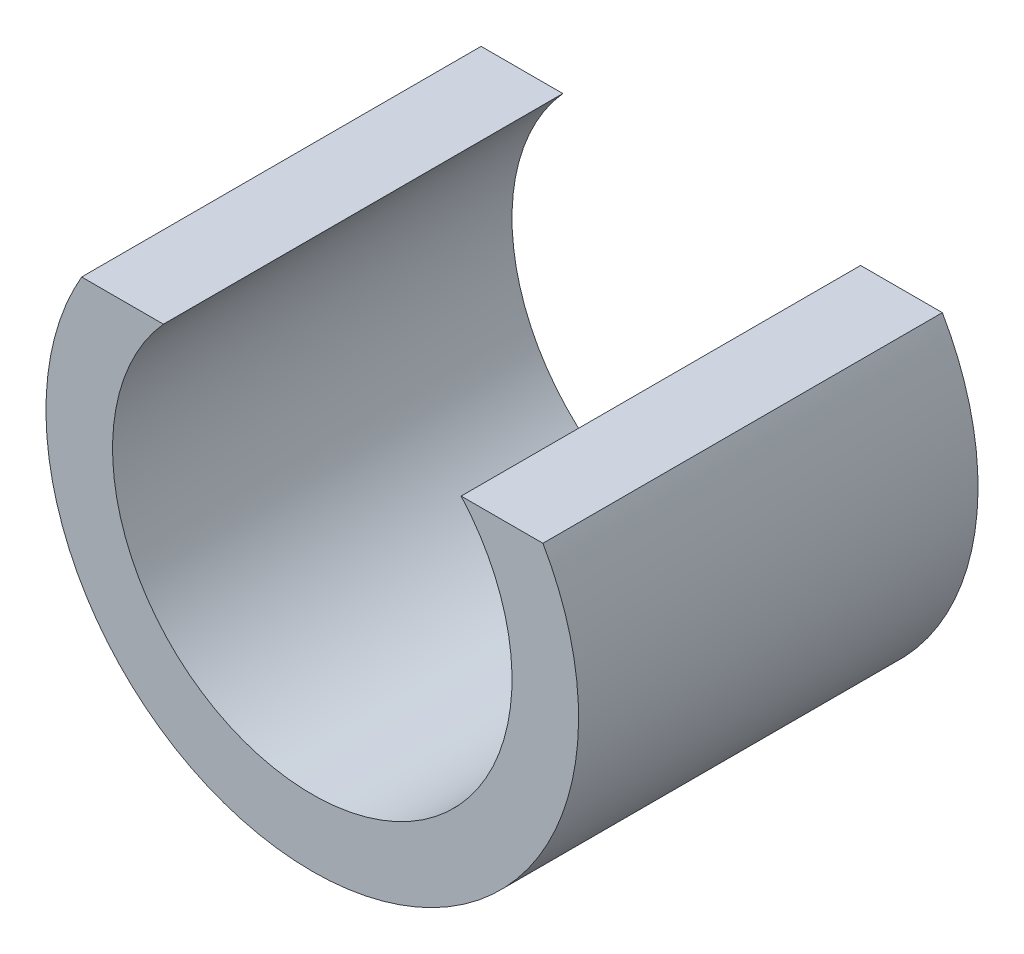
SolidWorks part; units mm, degrees
ref_plane "Спереди" through (0, 0, 0) normal (0, 0, 1) x (1, 0, 0)
ref_plane "Сверху" through (0, 0, 0) normal (0, 1, 0) x (1, 0, 0)
ref_plane "Справа" through (0, 0, 0) normal (1, 0, 0) x (0, 0, -1)
sketch "Sketch1" plane through (0, 0, 0) normal (0, 0, 1) x (1, 0, 0)
  circle A0 centre (0, 0) radius 2
extrude "Extrude1" add sketch "Sketch1" along normal blind 3
sketch "Sketch3" plane through (0, 0, 3) normal (0, 0, 1) x (1, 0, 0)
  line L0 (0, -1.5) -> (0, 1)
  line L1 (0, 1) -> (2.0607, 1)
  line L2 (2.0607, 1) -> (-2.0436, 1)
  line L3 (-2.0436, 1) -> (-2.0436, 2.1591)
  line L4 (-2.0436, 2.1591) -> (2.0607, 2.1591)
  line L5 (2.0607, 2.1591) -> (2.0607, 1)
  circle A0 centre (0, 0) radius 1.5
  circle M2 centre (0, 0) radius 2
extrude "Extrude3" cut sketch "Sketch3" against normal blind 3 contours L2 A0 L0 | L0 A0 L1 | L5 L4 L3 L2 L1 M2 | L1 A0 L2 | A0 L2 M2
